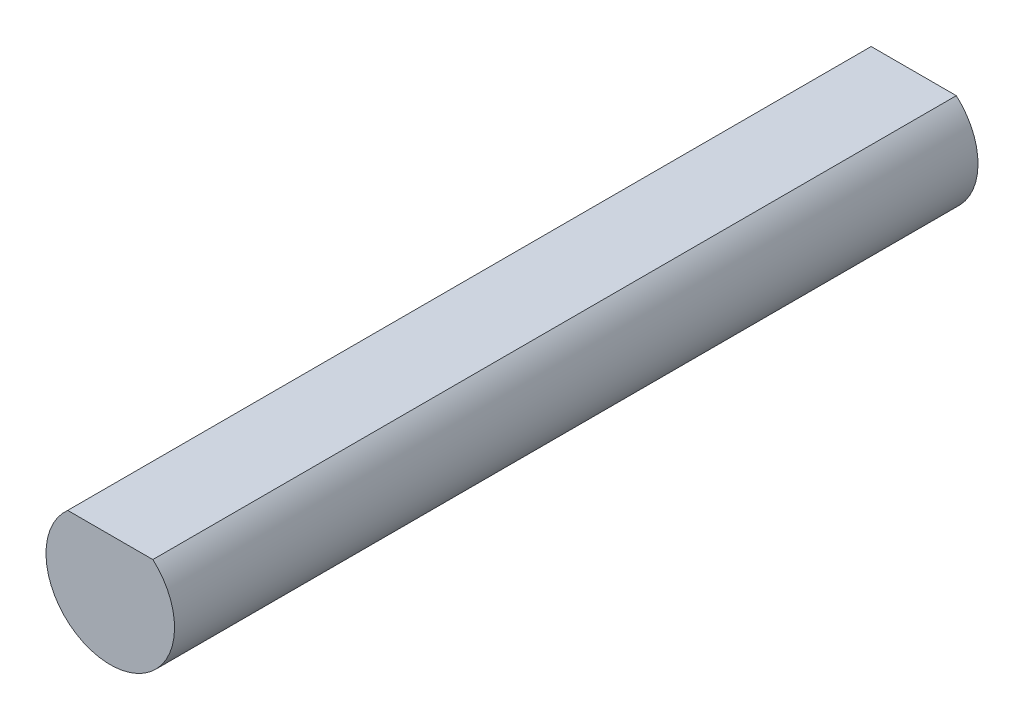
SolidWorks part; units mm, degrees
ref_plane "Front Plane" through (0, 0, 0) normal (0, 0, 1) x (1, 0, 0)
ref_plane "Top Plane" through (0, 0, 0) normal (0, 1, 0) x (1, 0, 0)
ref_plane "Right Plane" through (0, 0, 0) normal (1, 0, 0) x (0, 0, -1)
sketch "Sketch1" plane through (0, 0, 0) normal (0, 0, 1) x (1, 0, 0)
  line L0 (-1.325, 1.4981) -> (1.325, 1.4981)
  arc A0 (-1.325, 1.4981) -> (1.325, 1.4981) centre (0, 0) ccw
  dimension "D1" = 4
  dimension "D2" = 2.65
  dimension "D3" = 1.4981
extrude "Boss-Extrude1" add sketch "Sketch1" along normal blind 25
equation "\"height\"= 15mm"
equation "\"height 2\"= 25mm"
equation "\"D1@Boss-Extrude1\"=\"height 2\""
